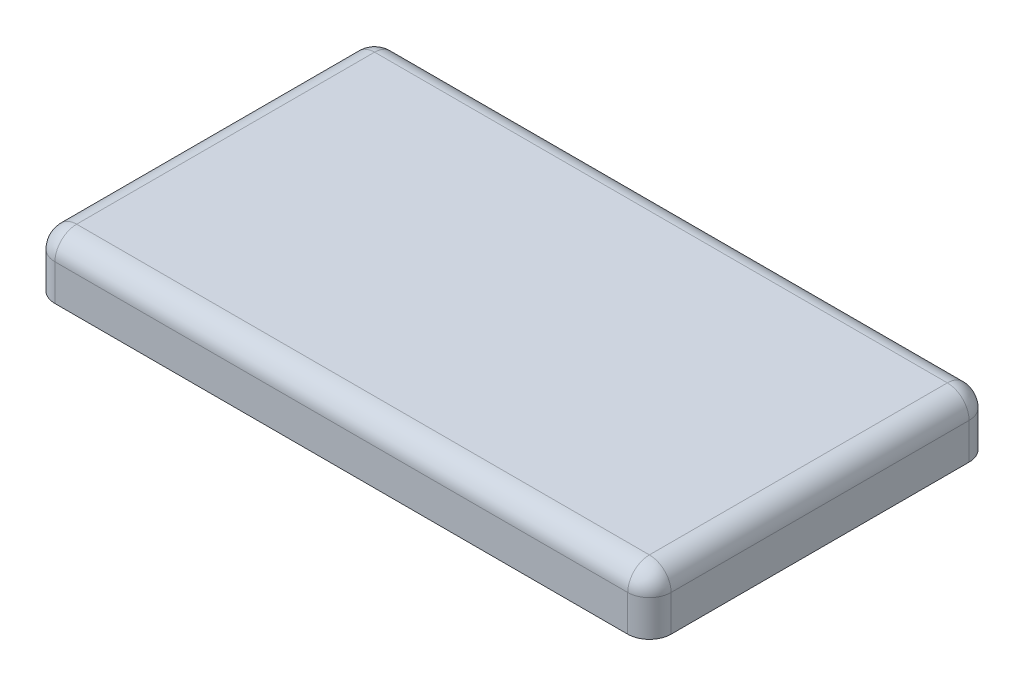
SolidWorks part; units mm, degrees
ref_plane "Front Plane" through (0, 0, 0) normal (0, 0, 1) x (1, 0, 0)
ref_plane "Top Plane" through (0, 0, 0) normal (0, 1, 0) x (1, 0, 0)
ref_plane "Right Plane" through (0, 0, 0) normal (1, 0, 0) x (0, 0, -1)
sketch "Sketch1" plane through (0, 0, 0) normal (0, 1, 0) x (1, 0, 0)
  line L1 (0, 0) -> (42.6, 0)
  line L2 (0, 0) -> (0, 23.6)
  line L3 (0, 23.6) -> (42.6, 23.6)
  line L4 (42.6, 0) -> (42.6, 23.6)
  dimension "D1" = 42.6
  dimension "D2" = 23.6
extrude "Boss-Extrude1" add sketch "Sketch1" along normal blind 4
sketch "Sketch2" plane through (0, 0, 0) normal (0, -1, 0) x (1, 0, 0)
  line L0 (21.3, 0) -> (21.3, -23.6) construction
  line L1 (0, 0) -> (42.6, 0) construction
  line L2 (42.6, -23.6) -> (0, -23.6) construction
  line L4 (1.25, -22.35) -> (41.35, -22.35)
  line L5 (1.25, -22.35) -> (1.25, -1.25)
  line L6 (1.25, -1.25) -> (41.35, -1.25)
  line L7 (41.35, -22.35) -> (41.35, -1.25)
  line L8 (1.25, -22.35) -> (41.35, -1.25) construction
  line L9 (1.25, -1.25) -> (41.35, -22.35) construction
  line L10 (0, -23.6) -> (42.6, -23.6) construction
  line L11 (0, -23.6) -> (0, 0) construction
  line L12 (0, 0) -> (42.6, 0) construction
  line L13 (42.6, -23.6) -> (42.6, 0) construction
  line L14 (0, -23.6) -> (42.6, 0) construction
  line L15 (0, 0) -> (42.6, -23.6) construction
  point P6 (21.3, -11.8)
  point P11 (21.3, -11.8)
  dimension "D1" = 1.25
  dimension "D2" = 1.25
extrude "Cut-Extrude1" cut sketch "Sketch2" against normal blind 2.6
fillet "Fillet1" radius 1.5 8 edges at (21.3, 4, -23.6) (42.6, 4, -11.8) (21.3, 4, 0) (0, 4, -11.8) (0, 2, 0) (0, 2, -23.6) (42.6, 2, -23.6) (42.6, 2, 0)
